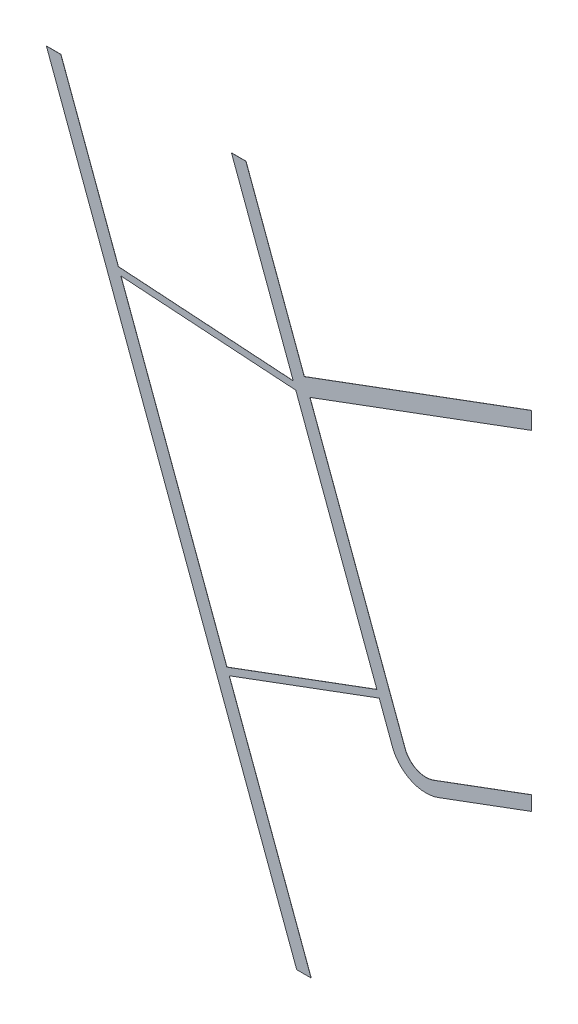
SolidWorks part; units mm, degrees
ref_plane "Front Plane" through (0, 0, 0) normal (0, 0, 1) x (1, 0, 0)
ref_plane "Top Plane" through (0, 0, 0) normal (0, 1, 0) x (1, 0, 0)
ref_plane "Right Plane" through (0, 0, 0) normal (1, 0, 0) x (0, 0, -1)
sketch "Sketch2" plane through (0, 0, 0) normal (0, 0, 1) x (1, 0, 0)
  line L1 (76038.761, -250000) -> (-109445.11, 250000)
  line L2 (86704.6743, -250000) -> (26009.0734, -86385.7714)
  line L5 (146955.4456, -71428.5814) -> (136459.21, -43134.3812)
  line L6 (156331.1078, -67950.5132) -> (85803.0786, 122168.522)
  line L9 (75362.2991, 121561.6396) -> (-54293.7379, 130082.6763)
  line L10 (73507.4604, 126561.6396) -> (-56148.5766, 135082.6763)
  line L12 (-20997.0947, 97829.6926) -> (32833.2448, -47278.1791) construction
  line L13 (-20997.0947, 97829.6926) -> (12180.289, 95649.2642) construction
  line L14 (24270.0393, -81697.9403) -> (24698.3388, -82852.487)
  line L15 (24270.0393, -81697.9403) -> (135462.9978, -40448.9396)
  line L16 (26009.0734, -86385.7714) -> (137202.032, -45136.7707)
  line L17 (136459.21, -43134.3812) -> (137202.032, -45136.7707)
  line L18 (81504.9155, 47500.0976) -> (66452.5436, 88076.0566) construction
  line L19 (250000, 250000) -> (-250000, 250000) construction
  line L21 (81629.3967, 133419.3167) -> (250000, 195879.3792)
  line L22 (85803.0786, 122168.522) -> (250000, 183080.2832)
  line L24 (250000, -250000) -> (250000, 250000) construction
  line L25 (-250000, -250000) -> (250000, -250000) construction
  line L26 (181012.4196, -87054.7224) -> (250000, -61462.5555)
  line L27 (177523.6375, -77674.1445) -> (250000, -50787.7519)
  line L28 (76038.761, -250000) -> (86704.6743, -250000)
  line L29 (250000, -61462.5555) -> (250000, -50787.7519)
  line L30 (27715.8106, 250000) -> (38381.7239, 250000)
  line L31 (250000, 183080.2832) -> (250000, 195879.3792)
  line L32 (-109445.11, 250000) -> (-98779.1967, 250000)
  line L33 (81629.3967, 133419.3167) -> (38381.7239, 250000)
  line L34 (-56148.5766, 135082.6763) -> (-98779.1967, 250000)
  line L35 (73507.4604, 126561.6396) -> (27715.8106, 250000)
  line L36 (24698.3388, -82852.487) -> (-54293.7379, 130082.6763)
  line L37 (135462.9978, -40448.9396) -> (75362.2991, 121561.6396)
  arc A0 (146955.4456, -71428.5814) -> (181012.4196, -87054.7224) centre (171797.0031, -62213.165) ccw
  arc A1 (156331.1078, -67950.5132) -> (177523.6375, -77674.1445) centre (171789.1883, -62216.064) ccw
  dimension "D1" = 10000
  dimension "D2" = 10000
  dimension "D3" = 5000
  dimension "D4" = 20000
  dimension "D5" = 20000
  dimension "D6" = 30000
  dimension "D7" = 5000
  dimension "D8" = 12000
extrude "Boss-Extrude1" add sketch "Sketch2" along normal blind 100 draft 1
